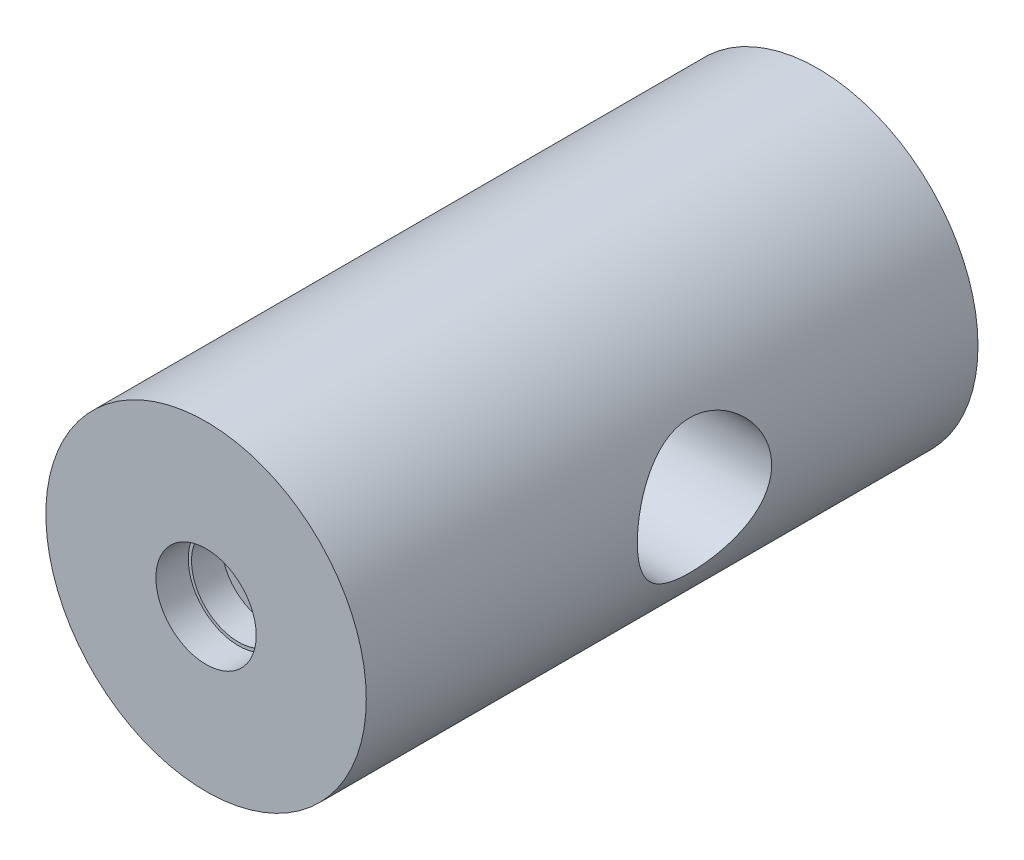
SolidWorks part; units mm, degrees
material "PET"
ref_plane "Piano frontale" through (0, 0, 0) normal (0, 0, 1) x (1, 0, 0)
ref_plane "Piano superiore" through (0, 0, 0) normal (0, 1, 0) x (1, 0, 0)
ref_plane "Piano destro" through (0, 0, 0) normal (1, 0, 0) x (0, 0, -1)
sketch "Schizzo1" plane through (0, 0, 0) normal (0, 0, 1) x (1, 0, 0)
  circle A0 centre (0, 0) radius 9.9
  dimension "D1" = 19.8
extrude "Estrusione-Estrusione1" add sketch "Schizzo1" along normal blind 29.8
sketch "Schizzo3" plane through (0, 0, 0) normal (1, 0, 0) x (0, 0, -1)
  line L0 (-29.8, 9.9) -> (-29.8, -9.9) construction
  line L1 (-29.8, 9.9) -> (-29.8, -9.9)
  line L2 (-29.8, 0) -> (-16.9, 0) construction
  circle A0 centre (-16.9, 0) radius 4.15
  dimension "D2" = 8.3
  dimension "D1" = 12.9
extrude "Taglio-Estrusione1" cut sketch "Schizzo3" against normal through all both and the other way through all contours A0
sketch "Schizzo5" plane through (0, 0, 29.8) normal (0, 0, 1) x (1, 0, 0)
  circle A1 centre (0, 0) radius 9.9
  circle A2 centre (0, 0) radius 9.9
  dimension "D1" = 0
extrude "Estrusione-Estrusione2" add sketch "Schizzo5" along normal blind 8
sketch "Schizzo6" plane through (0, 0, 37.8) normal (0, 0, 1) x (1, 0, 0)
  circle A0 centre (0, 0) radius 3.1
  dimension "D1" = 6.2
extrude "Taglio-Estrusione3" cut sketch "Schizzo6" against normal blind 2
sketch "Schizzo7" plane through (0, 0, 35.8) normal (0, 0, 1) x (1, 0, 0)
  circle A0 centre (0, 0) radius 2.9
  dimension "D1" = 5.8
extrude "Taglio-Estrusione4" cut sketch "Schizzo7" against normal blind 1.85
sketch "Schizzo8" plane through (0, 0, 33.95) normal (0, 0, 1) x (1, 0, 0)
  circle A0 centre (0, 0) radius 1.25
  dimension "D1" = 2.5
extrude "Taglio-Estrusione5" cut sketch "Schizzo8" against normal blind 10
